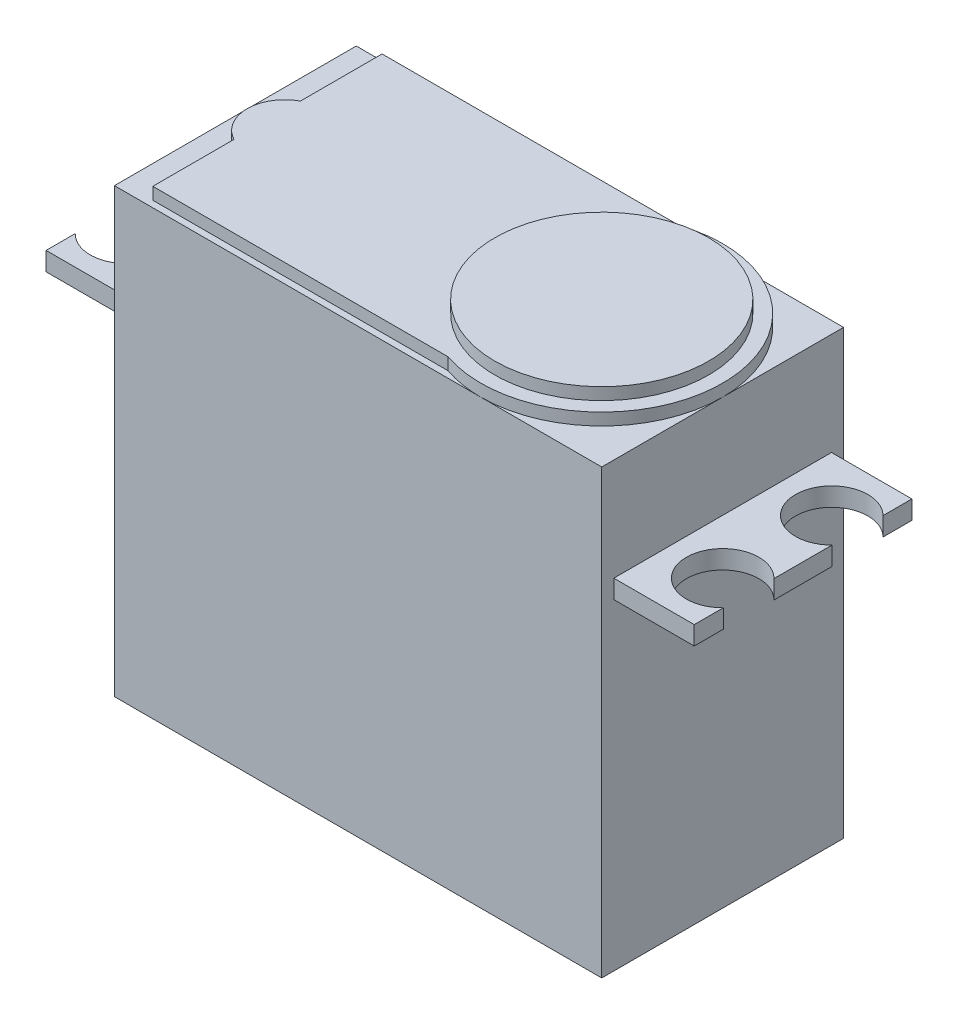
SolidWorks part; units mm, degrees
ref_plane "Front Plane" through (0, 0, 0) normal (0, 0, 1) x (1, 0, 0)
ref_plane "Top Plane" through (0, 0, 0) normal (0, 1, 0) x (1, 0, 0)
ref_plane "Right Plane" through (0, 0, 0) normal (1, 0, 0) x (0, 0, -1)
sketch "Sketch1" plane through (0, 0, 0) normal (0, 1, 0) x (1, 0, 0)
  line L1 (-26.0153, 10.3478) -> (14.2847, 10.3478)
  line L2 (-26.0153, 10.3478) -> (-26.0153, -9.6522)
  line L3 (-26.0153, -9.6522) -> (14.2847, -9.6522)
  line L4 (14.2847, 10.3478) -> (14.2847, -9.6522)
  dimension "D1" = 20
  dimension "D2" = 40.3
extrude "Boss-Extrude1" add sketch "Sketch1" along normal blind 36.6 contours L2 L3 L4 L1
sketch "Sketch5" plane through (0, 36.6, 0) normal (0, 1, 0) x (1, 0, 0)
  line L0 (-26.0153, 10.3478) -> (14.2847, 10.3478) construction
  line L1 (-23.3802, 9.8478) -> (1.1622, 9.8478)
  line L2 (-23.3802, 9.8478) -> (-23.3802, -9.1129)
  line L3 (-23.3802, -9.1129) -> (1.1622, -9.1129)
  line L4 (1.1622, 9.8478) -> (1.1622, -9.1129)
  line L7 (14.2847, 10.3478) -> (14.2847, -9.6522) construction
  circle A0 centre (4.2847, 0.3478) radius 10
  circle A1 centre (-21.9344, 0.3478) radius 3.1037
  dimension "D2" = 20
  dimension "D7" = 6.2073
  dimension "D1" = 18.9607
  dimension "D3" = 0.5
  dimension "D4" = 10
  dimension "D5" = 10
  dimension "D6" = 24.5424
  dimension "D8" = 1.4458
  dimension "D9" = 10
extrude "Boss-Extrude4" add sketch "Sketch5" along normal blind 1 contours L2 L3 L4 L1 | A1 | A0
sketch "Sketch7" plane through (0, 37.6, 0) normal (0, 1, 0) x (1, 0, 0)
  line L0 (4.2847, 10.3478) -> (14.2847, 10.3478) construction
  circle A0 centre (4.2847, 0.3478) radius 8.8409
  dimension "D1" = 10
  dimension "D2" = 10
extrude "Boss-Extrude5" add sketch "Sketch7" along normal blind 1 contours A0
sketch "Sketch8" plane through (-26.0153, 0, 0) normal (-1, 0, 0) x (0, 0, 1)
  line L0 (9.6522, 36.6) -> (9.6522, 0) construction
  line L1 (-9.3478, 28.1361) -> (8.6522, 28.1361)
  line L2 (-9.3478, 28.1361) -> (-9.3478, 26.6)
  line L3 (-9.3478, 26.6) -> (8.6522, 26.6)
  line L4 (8.6522, 28.1361) -> (8.6522, 26.6)
  line L5 (-10.3478, 0) -> (9.6522, 0) construction
  point P4 (8.6522, 27.368)
  dimension "D1" = 18
  dimension "D2" = 1.5361
  dimension "D3" = 1
  dimension "D4" = 26.6
extrude "Boss-Extrude7" add sketch "Sketch8" along normal blind 6.65 and the other way blind 46.95 contours L3 L4 L1 L2
sketch "Sketch10" plane through (0, 28.1361, 0) normal (0, 1, 0) x (1, 0, 0)
  line L1 (20.9347, 9.3478) -> (14.2847, 9.3478) construction
  line L2 (14.2847, 0.3478) -> (14.2847, -9.6522) construction
  line L3 (20.9347, -8.6522) -> (14.2847, -8.6522) construction
  circle A0 centre (18.8042, 4.8478) radius 3
  circle A1 centre (18.7847, -4.1521) radius 3
  dimension "D1" = 6
  dimension "D2" = 6
  dimension "D4" = 4.5
  dimension "D6" = 4.5
  dimension "D3" = 9
  dimension "D5" = 4.5
extrude "Cut-Extrude2" cut sketch "Sketch10" against normal through all
sketch "Sketch12" plane through (0, 28.1361, 0) normal (0, 1, 0) x (1, 0, 0)
  line L0 (-26.0153, -8.6522) -> (-32.6653, -8.6522) construction
  line L1 (-26.0153, 9.3478) -> (-26.0153, -8.6522) construction
  circle A0 centre (-30.5153, 4.8478) radius 3
  circle A1 centre (-30.5153, -4.1522) radius 3
  dimension "D1" = 6
  dimension "D2" = 6
  dimension "D5" = 4.5
  dimension "D3" = 9
  dimension "D4" = 4.5
  dimension "D6" = 4.5
extrude "Cut-Extrude3" cut sketch "Sketch12" against normal through all
sketch "Sketch13" plane through (0, 38.6, 0) normal (0, 1, 0) x (1, 0, 0)
  line L0 (-26.0153, -8.6522) -> (-26.0153, 9.3478) construction
  circle A0 centre (4.1891, 0.3478) radius 3
  dimension "D1" = 6
  dimension "D2" = 10
ref_plane "Plane1" through (-26.0153, 0, -10.3478) normal (0, -1, 0) x (-1, 0, 0)
sketch "Sketch16" plane through (-26.0153, 0, 0) normal (-1, 0, 0) x (0, 0, 1)
  line L0 (-10.3478, 0) -> (9.6522, 0) construction
  line L1 (-3.8478, 7) -> (3.1522, 7)
  line L2 (-3.8478, 7) -> (-3.8478, 4)
  line L3 (-3.8478, 4) -> (3.1522, 4)
  line L4 (3.1522, 7) -> (3.1522, 4)
  line L5 (9.6522, 36.6) -> (9.6522, 0) construction
  dimension "D1" = 7
  dimension "D2" = 3
  dimension "D3" = 4
  dimension "D4" = 6.5
extrude "Boss-Extrude8" add sketch "Sketch16" along normal blind 5 contours L4 L3 L2 L1
